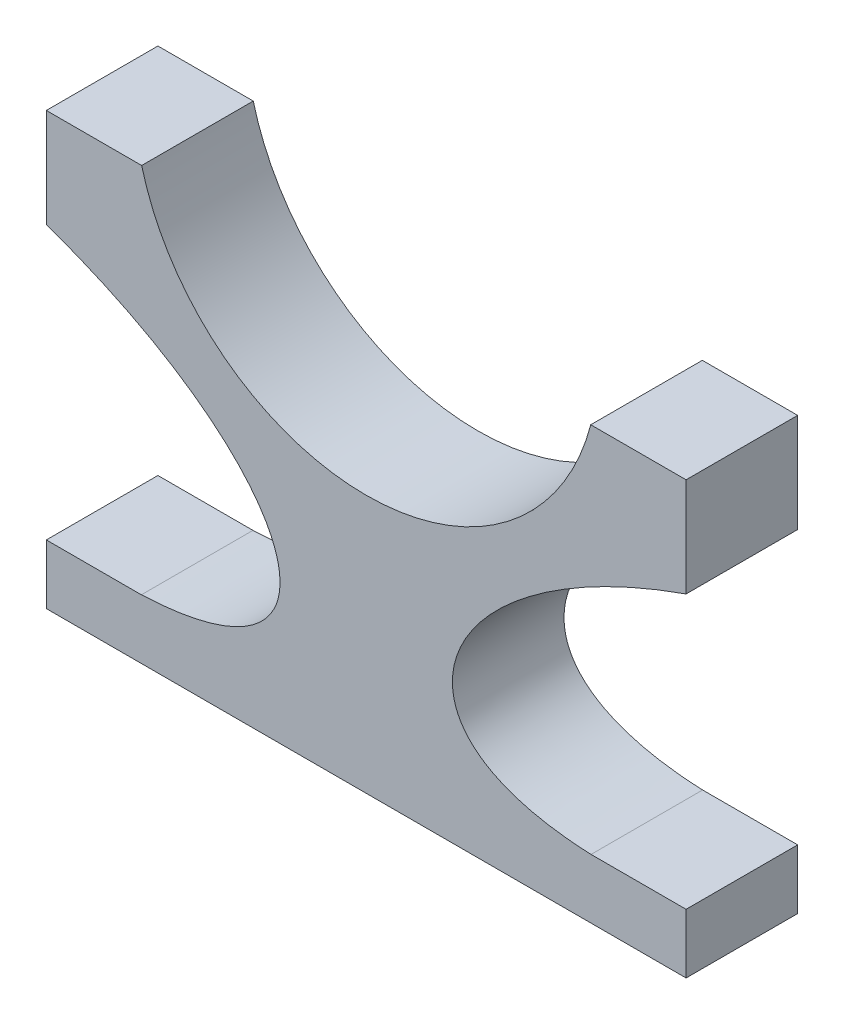
SolidWorks part; units mm, degrees
ref_plane "Спереди" through (0, 0, 0) normal (0, 0, 1) x (1, 0, 0)
ref_plane "Сверху" through (0, 0, 0) normal (0, 1, 0) x (1, 0, 0)
ref_plane "Справа" through (0, 0, 0) normal (1, 0, 0) x (0, 0, -1)
sketch "Эскиз1" plane through (0, 0, 0) normal (0, 0, 1) x (1, 0, 0)
  line L1 (0, 0) -> (86, 0)
  line L2 (0, 0) -> (0, -58)
  line L3 (0, -58) -> (86, -58)
  line L4 (86, 0) -> (86, -58)
extrude "Вытянуть1" add sketch "Эскиз1" along normal blind 15
sketch "Эскиз2" plane through (0, 0, 0) normal (0, 1, 0) x (1, 0, 0)
  line L0 (45, 0) -> (45, 13.8293) construction
sketch "Эскиз3" plane through (0, 0, 0) normal (0, 0, 1) x (1, 0, 0)
  line L0 (43, 0) -> (43, -74.8104) construction
  circle A0 centre (43, 7.8963) radius 31.2
extrude "Вырез-Вытянуть1" cut sketch "Эскиз3" along normal blind 32
sketch "Эскиз6" plane through (0, 0, 15) normal (0, 0, 1) x (1, 0, 0)
  line L0 (43, -23.3037) -> (43, 0) construction
  line L1 (0, -50) -> (14.2522, -50) construction
  line L4 (0, 0) -> (0, -58) construction
  line L5 (0, -50) -> (12.7756, -50)
  line L6 (86, -50) -> (73.2244, -50)
  line L7 (0, -13.2928) -> (-6.7369, -13.2928)
  line L8 (-6.7369, -13.2928) -> (-6.7369, -50)
  line L9 (-6.7369, -50) -> (0, -50)
  line L10 (92.7369, -50) -> (86, -50)
  line L11 (92.7369, -13.2928) -> (92.7369, -50)
  line L12 (86, -13.2928) -> (92.7369, -13.2928)
  spline S0 degree 3 poles (0, -13.2928) (34.6579, -25.4671) (43.1335, -48.7313) (12.7756, -50) knots 0 0 0 0 0.93658 0.93658 0.93658 0.93658
  spline S1 degree 3 poles (86, -13.2928) (51.3421, -25.4671) (42.8665, -48.7313) (73.2244, -50) knots 0 0 0 0 0.93658 0.93658 0.93658 0.93658
extrude "Вытянуть2" cut sketch "Эскиз6" against normal blind 32
